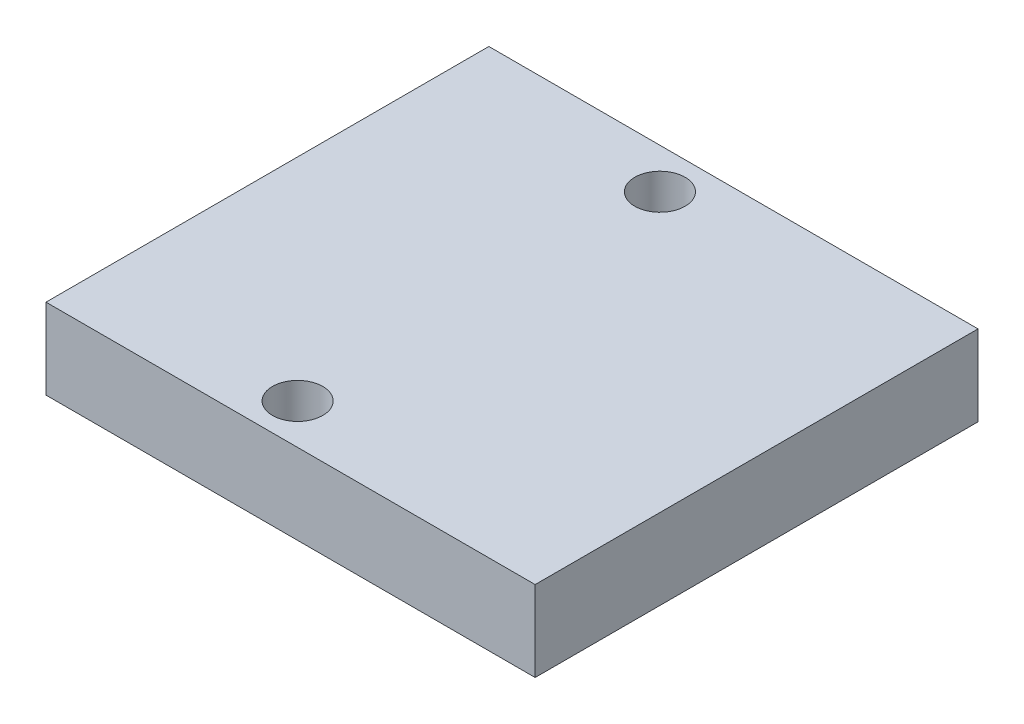
SolidWorks part; units mm, degrees
ref_plane "Front Plane" through (0, 0, 0) normal (0, 0, 1) x (1, 0, 0)
ref_plane "Top Plane" through (0, 0, 0) normal (0, 1, 0) x (1, 0, 0)
ref_plane "Right Plane" through (0, 0, 0) normal (1, 0, 0) x (0, 0, -1)
sketch "Sketch1" plane through (0, 0, 0) normal (0, 1, 0) x (1, 0, 0)
  line L0 (-12.15, 0) -> (12.15, 0) construction
  line L1 (-12.15, 11) -> (12.15, 11)
  line L2 (-12.15, 11) -> (-12.15, -11)
  line L3 (-12.15, -11) -> (12.15, -11)
  line L4 (12.15, 11) -> (12.15, -11)
  line L5 (0, 11) -> (0, -11) construction
  circle A0 centre (-1.65, 9) radius 1.25
  circle A1 centre (-1.65, -9) radius 1.25
  point P0 (0, 0)
  point P6 (-34.5576, 9)
  dimension "D2" = 2.5
  dimension "D1" = 22
  dimension "D3" = 24.3
  dimension "D4" = 9
  dimension "D5" = 10.5
extrude "Boss-Extrude1" add sketch "Sketch1" along normal blind 4
equation "\"D3@Sketch1\"=2.43"
